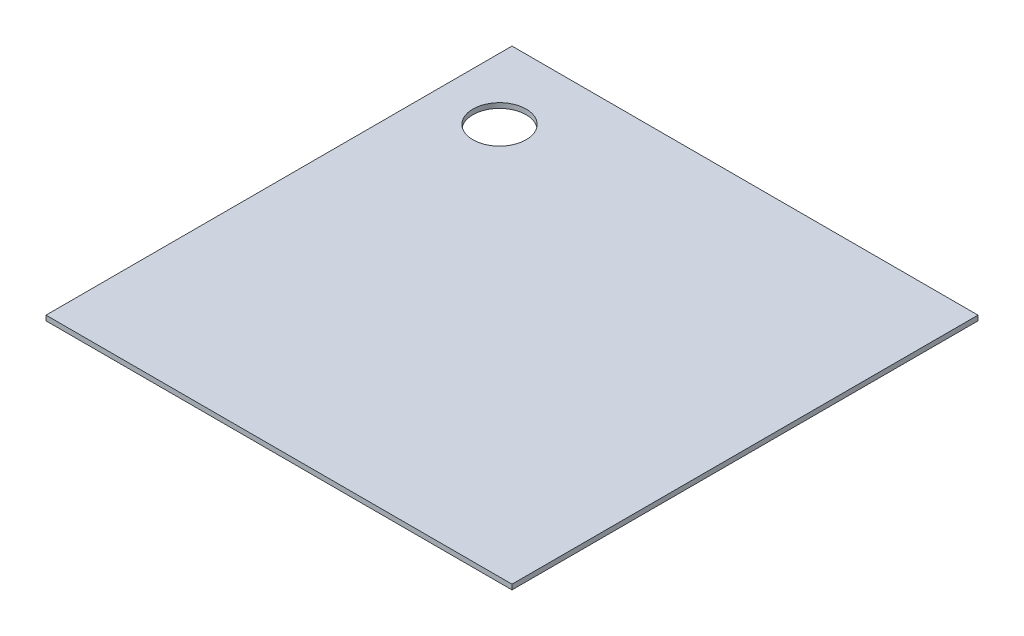
SolidWorks part; units mm, degrees
ref_plane "Front Plane" through (0, 0, 0) normal (0, 0, 1) x (1, 0, 0)
ref_plane "Top Plane" through (0, 0, 0) normal (0, 1, 0) x (1, 0, 0)
ref_plane "Right Plane" through (0, 0, 0) normal (1, 0, 0) x (0, 0, -1)
sketch "Sketch1" plane through (0, 0, 0) normal (0, 1, 0) x (1, 0, 0)
  line L1 (140, -140) -> (-140, -140)
  line L2 (140, -140) -> (140, 140)
  line L3 (140, 140) -> (-140, 140)
  line L4 (-140, -140) -> (-140, 140)
  line L5 (140, -140) -> (-140, 140) construction
  line L6 (140, 140) -> (-140, -140) construction
  circle A0 centre (-103, 95.5) radius 12.5 construction
  circle A2 centre (-103, 95.5) radius 16
  point P0 (0, 0)
  dimension "D2" = 25
  dimension "D4" = 24.5
  dimension "D5" = 32
  dimension "D3" = 32
  dimension "D1" = 280
extrude "Boss-Extrude1" add sketch "Sketch1" along normal mid plane 3
